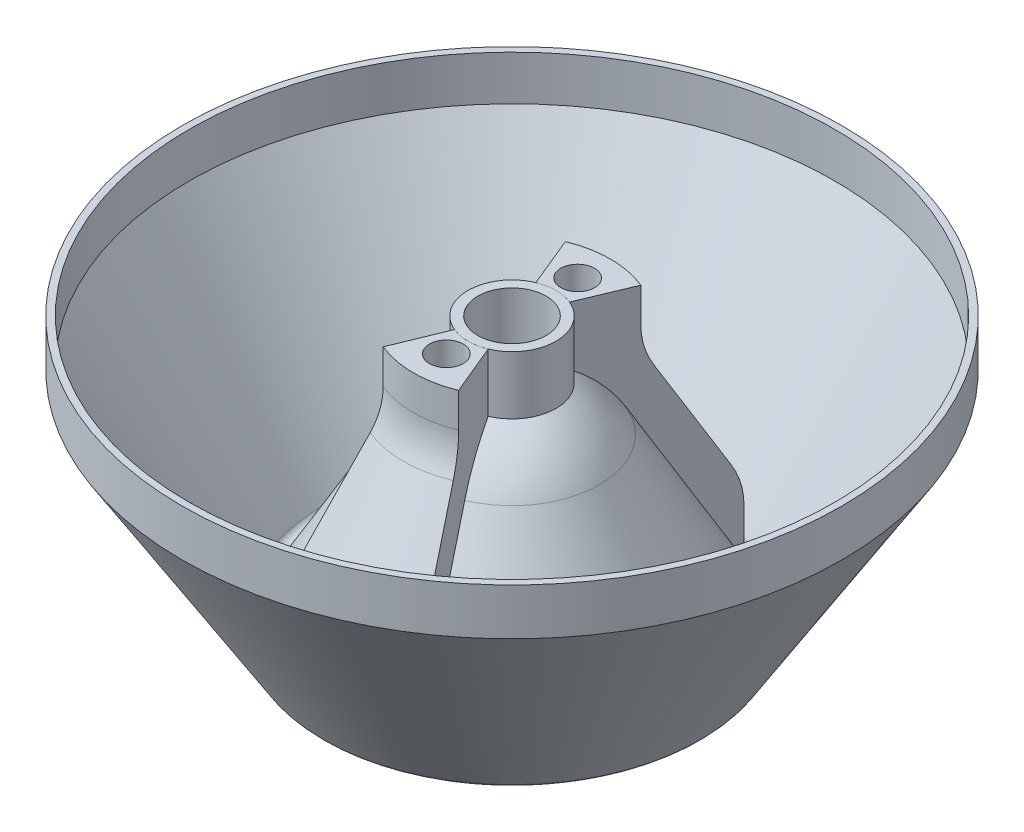
SolidWorks part; units mm, degrees
ref_plane "Front Plane" through (0, 0, 0) normal (0, 0, 1) x (1, 0, 0)
ref_plane "Top Plane" through (0, 0, 0) normal (0, 1, 0) x (1, 0, 0)
ref_plane "Right Plane" through (0, 0, 0) normal (1, 0, 0) x (0, 0, -1)
sketch "Sketch1" plane through (0, 0, 0) normal (1, 0, 0) x (0, 0, -1)
  line L0 (-48.729, 20.833) -> (-48.729, 13.9354)
  line L5 (-48.729, 20.833) -> (48.729, 20.833) construction
  line L6 (-48.729, 20.833) -> (-48.729, -20.833) construction
  line L7 (-48.729, -20.833) -> (48.729, -20.833) construction
  line L8 (48.729, 20.833) -> (48.729, -20.833) construction
  line L9 (-48.729, 20.833) -> (48.729, -20.833) construction
  line L10 (-48.729, -20.833) -> (48.729, 20.833) construction
  line L11 (-48.729, 13.9354) -> (-27.9212, -19.4195)
  line L12 (-47.729, 20.833) -> (-47.729, 14.2217)
  line L13 (-47.729, 14.2217) -> (-27.9545, -17.4768)
  line L14 (-26.24, -17.4475) -> (-12.9089, 5.6485)
  line L15 (-26.2067, -19.3902) -> (-12.0428, 5.1486)
  line L16 (-47.729, 14.2217) -> (-27.0728, -18.8903) construction
  line L17 (-27.0728, -18.8903) -> (-12.9089, 5.6485) construction
  line L18 (-47.729, 20.833) -> (-48.729, 20.833)
  line L19 (0, 0) -> (0, -20.833) construction
  line L24 (-6.5023, 20.833) -> (-6.5023, 12.2224)
  line L29 (-5.0525, 20.833) -> (-6.5023, 20.833)
  line L30 (-5.0525, 20.833) -> (-5.0525, 11.8994)
  arc A0 (-27.9212, -19.4195) -> (-26.2067, -19.3902) centre (-27.0728, -18.8903) ccw
  arc A1 (-12.0428, 5.1486) -> (-5.0525, 11.8994) centre (3.2196, -3.6609) cw
  arc A2 (-12.9089, 5.6485) -> (-0.1361, 14.6567) centre (3.2196, -3.6609) cw construction
  arc A3 (-12.9089, 5.6485) -> (-6.5023, 12.2224) centre (3.2196, -3.6609) cw
  arc A4 (-27.9545, -17.4768) -> (-26.24, -17.4475) centre (-27.1061, -16.9476) ccw
  arc A5 (-27.0728, -18.8903) -> (-27.0728, -18.8903) centre (-27.0728, -18.8903) ccw construction
  arc A6 (-12.0428, 5.1486) -> (0.0441, 13.6731) centre (3.2196, -3.6609) cw construction
  point P0 (0, 0)
  point P14 (-27.0395, -20.833)
  point P27 (-1.6138, 11.8994)
  point P29 (0, 0)
  point P30 (0, 0)
  point P31 (0, 0)
  point P32 (-5.0525, 17.5)
  point P36 (0, 0)
  point P37 (0, 0)
  point P38 (0, 0)
  point P39 (0, 0)
  point P40 (0, 0)
  point P41 (-5.0525, 11.8362)
  point P42 (0, 0)
  dimension "D1" = 1
  dimension "D3" = 1
  dimension "D2" = 1
revolve "Revolve7" add sketch "Sketch1" angle 360 about L19
sketch "Sketch4" plane through (0, 0, 0) normal (1, 0, 0) x (0, 0, -1)
  line L2 (-26.24, -17.4475) -> (-26.24, -10.3923)
  line L5 (0, 0) -> (0, -20.833) construction
  line L7 (-30.5704, -14.9479) -> (-17.2393, 8.1481)
  line L8 (-24.7669, -4.8934) -> (-16.0437, 10.2195)
  line L9 (-14.5706, 15.7184) -> (-14.5706, 20.8073)
  line L10 (-14.5706, 20.8073) -> (-6.5023, 20.833)
  line L11 (-26.24, -17.4475) -> (-12.9089, 5.6485)
  line L12 (-26.24, -17.4475) -> (-12.9089, 5.6485)
  line L13 (-6.5023, 20.833) -> (-6.5023, 12.2224)
  arc A2 (-24.7669, -4.8934) -> (-26.24, -10.3923) centre (-15.24, -10.3923) ccw
  arc A5 (-9.1126, 16.4869) -> (-17.2393, 8.1481) centre (3.2196, -3.6609) ccw
  arc A8 (-14.5706, 15.7184) -> (-16.0437, 10.2195) centre (-25.5706, 15.7184) cw
  arc A10 (-6.5023, 12.2224) -> (-12.9089, 5.6485) centre (3.2196, -3.6609) ccw
  arc A11 (-6.5023, 12.2224) -> (-12.9089, 5.6485) centre (3.2196, -3.6609) ccw
  point P2 (0, 0)
  point P6 (-14.3429, 13.166)
  dimension "D2" = 11
  dimension "D3" = 5
  dimension "D1" = 11
  dimension "D4" = 0
  dimension "D5" = 0
revolve "Revolve9" add sketch "Sketch4" angle 45 mid plane about L5
sketch "Sketch6" plane through (0, 0, 0) normal (1, 0, 0) x (0, 0, -1)
  line L139 (-23.9008, -5.3933) -> (-15.1776, 9.7196)
  line L140 (-23.9008, -5.3933) -> (-15.1776, 9.7196)
  line L142 (-25.24, -17.4475) -> (-25.24, -10.3923)
  line L143 (-25.24, -13.7146) -> (-25.24, -10.3923)
  line L144 (-7.0244, 13.0753) -> (-13.8653, 13.0753)
  line L145 (-27.1061, -16.9476) -> (-13.775, 6.1484)
  line L146 (-25.24, -13.7146) -> (-13.775, 6.1484)
  arc A80 (-23.9008, -5.3933) -> (-25.24, -10.3923) centre (-15.24, -10.3923) ccw
  arc A81 (-23.9008, -5.3933) -> (-25.24, -10.3923) centre (-15.24, -10.3923) ccw
  arc A83 (-7.0244, 13.0753) -> (-13.775, 6.1484) centre (3.2196, -3.6609) ccw
  arc A84 (-7.0244, 13.0753) -> (-13.775, 6.1484) centre (3.2196, -3.6609) ccw
  arc A86 (-15.1776, 9.7196) -> (-13.5706, 15.7184) centre (-25.5706, 15.7184) ccw
  arc A87 (-15.1776, 9.7196) -> (-13.8653, 13.0753) centre (-25.5706, 15.7184) ccw
  point P2 (0, 0)
  dimension "D1" = 1
  dimension "D2" = 1
  dimension "D3" = 1
  dimension "D4" = 1
  dimension "D5" = 1
  dimension "D6" = 1
revolve "Cut-Revolve4" cut sketch "Sketch6" angle 30 mid plane about L19
sketch "Sketch11" plane through (0, 13.0753, 0) normal (0, -1, 0) x (1, 0, 0)
  line L0 (0, 6.5023) -> (0, 12.9089) construction
  circle A0 centre (0, 9.7056) radius 2.5
extrude "Cut-Extrude1" cut sketch "Sketch11" against normal blind 10
pattern_circular "CirPattern12" count 2 over 180 about axis through (0, 0, 0) along (0, 1, 0) of bodies 109 106
